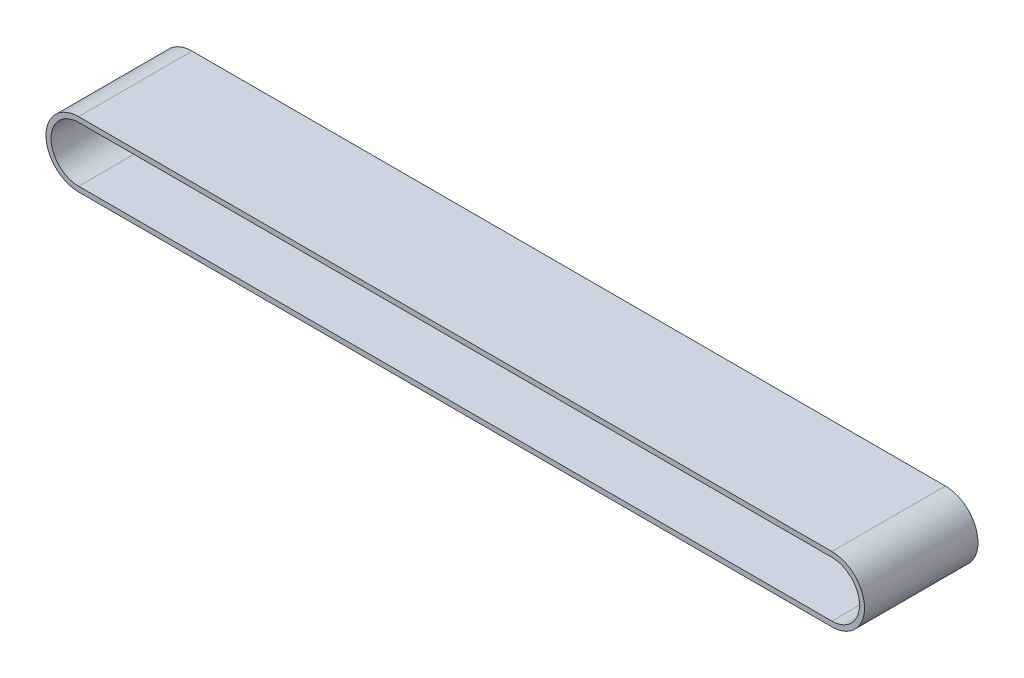
SolidWorks part; units mm, degrees
ref_plane "Front Plane" through (0, 0, 0) normal (0, 0, 1) x (1, 0, 0)
ref_plane "Top Plane" through (0, 0, 0) normal (0, 1, 0) x (1, 0, 0)
ref_plane "Right Plane" through (0, 0, 0) normal (1, 0, 0) x (0, 0, -1)
sketch "Esquisse1" plane through (0, 0, 0) normal (0, 0, 1) x (1, 0, 0)
  line L0 (-375, 0) -> (375, 0) construction
  line L1 (-375, 32.5) -> (375, 32.5)
  line L2 (-375, -32.5) -> (375, -32.5)
  line L3 (-375, 27.5) -> (375, 27.5)
  line L4 (-375, -27.5) -> (375, -27.5)
  arc A0 (-375, 32.5) -> (-375, -32.5) centre (-375, 0) ccw
  arc A1 (375, -32.5) -> (375, 32.5) centre (375, 0) ccw
  arc A2 (375, -27.5) -> (375, 27.5) centre (375, 0) ccw
  arc A3 (-375, 27.5) -> (-375, -27.5) centre (-375, 0) ccw
  point P3 (0, 0)
  dimension "D1" = 750
  dimension "D2" = 65
  dimension "D3" = 5
extrude "Boss.-Extru.1" add sketch "Esquisse1" along normal blind 113
